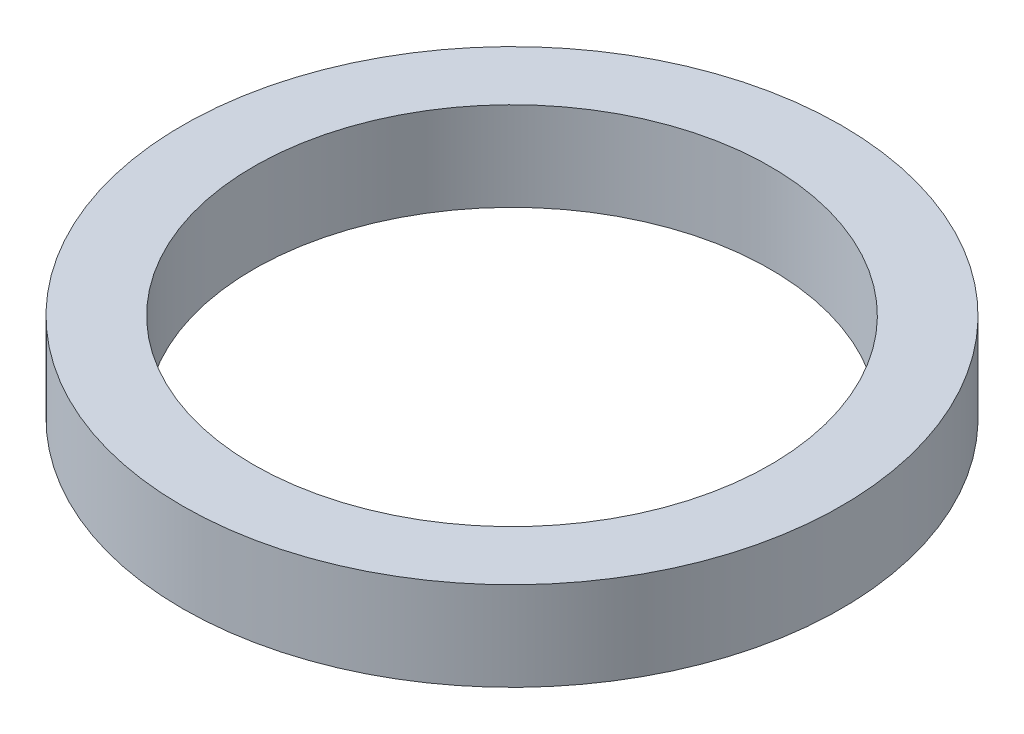
SolidWorks part; units mm, degrees
ref_plane "Front Plane" through (0, 0, 0) normal (0, 0, 1) x (1, 0, 0)
ref_plane "Top Plane" through (0, 0, 0) normal (0, 1, 0) x (1, 0, 0)
ref_plane "Right Plane" through (0, 0, 0) normal (1, 0, 0) x (0, 0, -1)
sketch "Sketch1" plane through (0, 0, 0) normal (0, 1, 0) x (1, 0, 0)
  circle A0 centre (0, 0) radius 17.15
  circle A1 centre (0, 0) radius 21.875
  dimension "D1" = 34.3
  dimension "D2" = 43.75
extrude "Boss-Extrude1" add sketch "Sketch1" along normal blind 5.9
